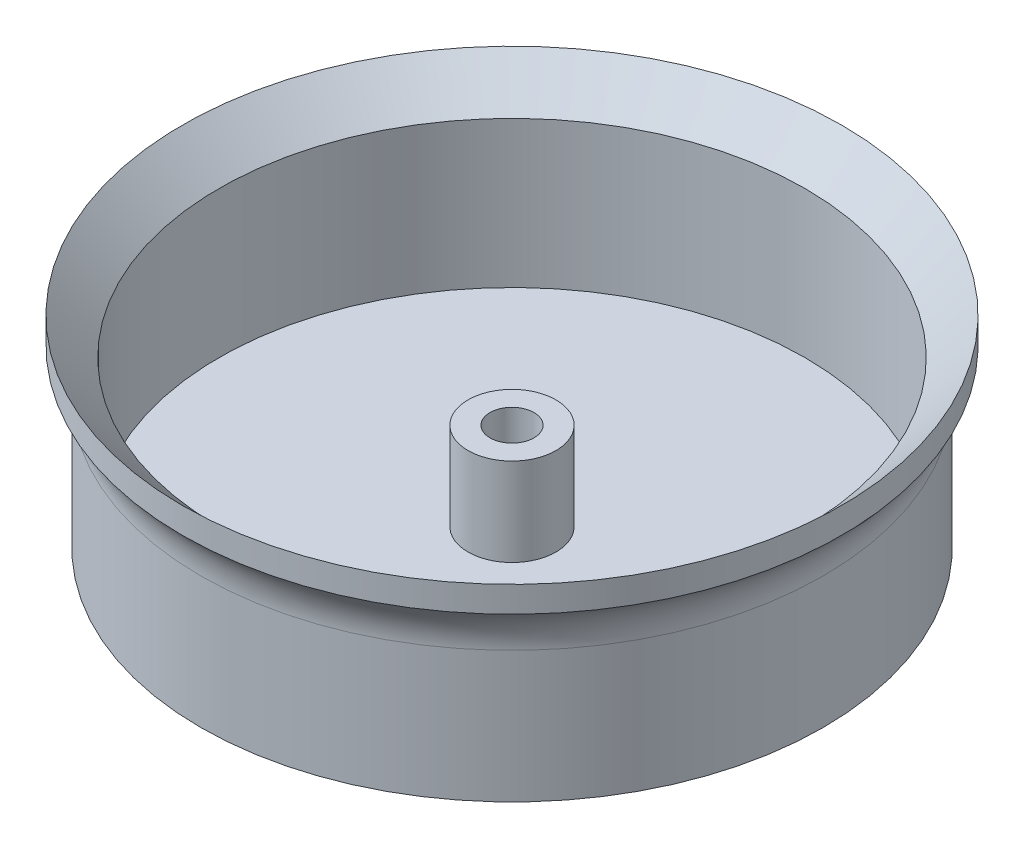
SolidWorks part; units mm, degrees
ref_plane "Front Plane" through (0, 0, 0) normal (0, 0, 1) x (1, 0, 0)
ref_plane "Top Plane" through (0, 0, 0) normal (0, 1, 0) x (1, 0, 0)
ref_plane "Right Plane" through (0, 0, 0) normal (1, 0, 0) x (0, 0, -1)
sketch "Sketch2" plane through (0, 0, 0) normal (1, 0, 0) x (0, 0, -1)
  line L0 (0, 0) -> (0, -6.0614) construction
  line L1 (1.905, 0) -> (1.905, 9.2075)
  line L2 (1.905, 9.2075) -> (3.81, 9.2075)
  line L3 (3.81, 9.2075) -> (3.81, 1.5875)
  line L4 (3.81, 1.5875) -> (25.4, 1.5875)
  line L5 (25.4, 1.5875) -> (25.4, 14.2875)
  line L6 (25.4, 14.2875) -> (28.575, 17.4625)
  line L7 (28.575, 17.4625) -> (28.575, 15.2174)
  line L9 (26.9875, 11.3849) -> (26.9875, 0)
  line L10 (26.9875, 0) -> (1.905, 0)
  line L11 (28.575, 15.2174) -> (24.9162, 11.5586) construction
  arc A0 (28.575, 15.2174) -> (26.9875, 11.3849) centre (32.4076, 11.3849) ccw
  point P2 (0, 0)
  point P5 (1.6179, 0)
  point P15 (0, 0)
  point P16 (0, 0)
  point P17 (1.1477, 9.2075)
  point P18 (1.8392, 8.4362)
  point P19 (0, 0)
  dimension "D1" = 1.5875
  dimension "D2" = 1.5875
  dimension "D3" = 50.8
  dimension "D4" = 7.62
  dimension "D5" = 7.62
  dimension "D6" = 12.7
  dimension "D7" = 1.5875
  dimension "D8" = 3.175
  dimension "D9" = 45
  dimension "D10" = 3.81
revolve "Revolve1" add sketch "Sketch2" angle 360 about L0
